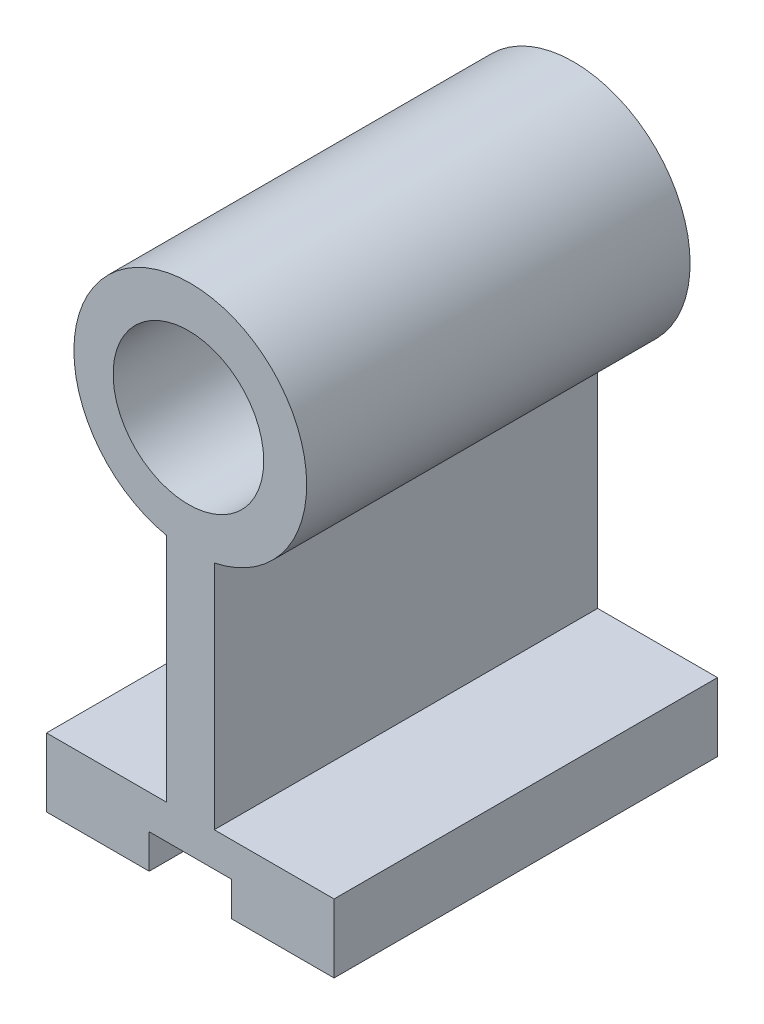
SolidWorks part; units mm, degrees
material "Commercially Pure CP-Ti UNS R50400 (SS)"
ref_plane "Front Plane" through (0, 0, 0) normal (0, 0, 1) x (1, 0, 0)
ref_plane "Top Plane" through (0, 0, 0) normal (0, 1, 0) x (1, 0, 0)
ref_plane "Right Plane" through (0, 0, 0) normal (1, 0, 0) x (0, 0, -1)
sketch "Sketch3" plane through (0, 0, 0) normal (0, 0, 1) x (1, 0, 0)
  line L0 (0, 0) -> (-15, 0)
  line L1 (-15, 0) -> (-15, 10)
  line L2 (-15, 10) -> (2.5, 10)
  line L3 (2.5, 10) -> (2.5, 43.7506)
  line L5 (9.5, 43.7506) -> (9.5, 10)
  line L6 (9.5, 10) -> (27, 10)
  line L7 (27, 10) -> (27, 0)
  line L8 (27, 0) -> (12, 0)
  line L9 (12, 0) -> (12, 5)
  line L10 (12, 5) -> (0, 5)
  line L11 (0, 5) -> (0, 0)
  line L12 (-3.3179, 52) -> (-1.5402, 52) construction
  arc A2 (9.5, 43.7506) -> (2.5, 43.7506) centre (6, 60.3864) ccw
  circle A3 centre (5.728, 60.2567) radius 11
  point P3 (12, 2.5)
  point P20 (0, 0)
  dimension "D7" = 34
  dimension "D8" = 22
  dimension "D1" = 42
  dimension "D2" = 10
  dimension "D3" = 12
  dimension "D4" = 7
  dimension "D5" = 5
  dimension "D6" = 52
  dimension "D9" = 21
  dimension "D10" = 5
extrude "Boss-Extrude1" add sketch "Sketch3" along normal blind 56
